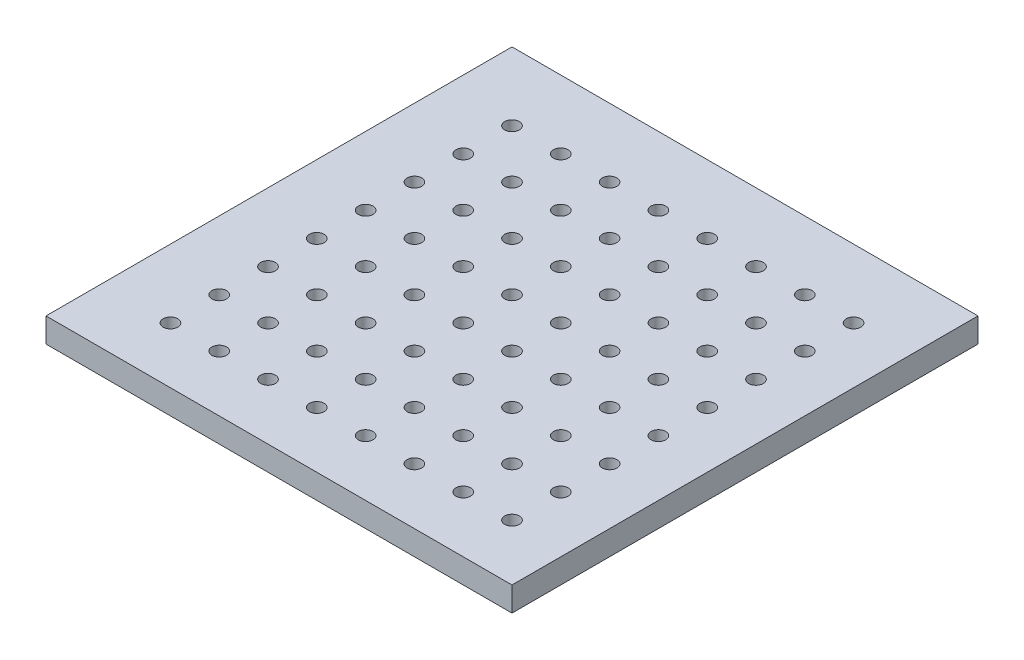
SolidWorks part; units mm, degrees
ref_plane "Front Plane" through (0, 0, 0) normal (0, 0, 1) x (1, 0, 0)
ref_plane "Top Plane" through (0, 0, 0) normal (0, 1, 0) x (1, 0, 0)
ref_plane "Right Plane" through (0, 0, 0) normal (1, 0, 0) x (0, 0, -1)
sketch "Sketch1" plane through (0, 0, 0) normal (0, 1, 0) x (1, 0, 0)
  line L0 (28, 163) -> (48, 163) construction
  line L1 (0, 0) -> (191, 0)
  line L2 (0, 0) -> (0, 191)
  line L3 (0, 191) -> (191, 191)
  line L4 (191, 0) -> (191, 191)
  line L5 (28, 163) -> (28, 143) construction
  circle A4 centre (28, 163) radius 3
  circle A5 centre (48, 163) radius 3
  circle A6 centre (68, 163) radius 3
  circle A7 centre (88, 163) radius 3
  circle A8 centre (108, 163) radius 3
  circle A22 centre (48, 143) radius 3
  circle A23 centre (68, 143) radius 3
  circle A24 centre (88, 143) radius 3
  circle A25 centre (108, 143) radius 3
  circle A39 centre (48, 123) radius 3
  circle A40 centre (68, 123) radius 3
  circle A41 centre (88, 123) radius 3
  circle A42 centre (108, 123) radius 3
  circle A56 centre (48, 103) radius 3
  circle A57 centre (68, 103) radius 3
  circle A58 centre (88, 103) radius 3
  circle A59 centre (108, 103) radius 3
  circle A73 centre (48, 83) radius 3
  circle A74 centre (68, 83) radius 3
  circle A75 centre (88, 83) radius 3
  circle A76 centre (108, 83) radius 3
  circle A311 centre (28, 143) radius 3
  circle A312 centre (28, 123) radius 3
  circle A313 centre (28, 103) radius 3
  circle A314 centre (28, 83) radius 3
  circle A328 centre (28, 63) radius 3
  circle A329 centre (48, 63) radius 3
  circle A330 centre (68, 63) radius 3
  circle A331 centre (88, 63) radius 3
  circle A332 centre (108, 63) radius 3
  circle A333 centre (28, 43) radius 3
  circle A334 centre (48, 43) radius 3
  circle A335 centre (68, 43) radius 3
  circle A336 centre (88, 43) radius 3
  circle A337 centre (108, 43) radius 3
  circle A338 centre (28, 23) radius 3
  circle A339 centre (48, 23) radius 3
  circle A340 centre (68, 23) radius 3
  circle A341 centre (88, 23) radius 3
  circle A342 centre (108, 23) radius 3
  circle A343 centre (128, 163) radius 3
  circle A344 centre (148, 163) radius 3
  circle A345 centre (168, 163) radius 3
  circle A346 centre (128, 143) radius 3
  circle A347 centre (148, 143) radius 3
  circle A348 centre (168, 143) radius 3
  circle A349 centre (128, 123) radius 3
  circle A350 centre (148, 123) radius 3
  circle A351 centre (168, 123) radius 3
  circle A352 centre (128, 103) radius 3
  circle A353 centre (148, 103) radius 3
  circle A354 centre (168, 103) radius 3
  circle A355 centre (128, 83) radius 3
  circle A356 centre (148, 83) radius 3
  circle A357 centre (168, 83) radius 3
  circle A358 centre (128, 63) radius 3
  circle A359 centre (148, 63) radius 3
  circle A360 centre (168, 63) radius 3
  circle A361 centre (128, 43) radius 3
  circle A362 centre (148, 43) radius 3
  circle A363 centre (168, 43) radius 3
  circle A364 centre (128, 23) radius 3
  circle A365 centre (148, 23) radius 3
  circle A366 centre (168, 23) radius 3
  point P7 (18.003, 169.1432)
  point P109 (0, 0)
  dimension "D7" = 6
  dimension "D1" = 191
  dimension "D2" = 191
  dimension "D5" = 20
  dimension "D6" = 20
  dimension "D8" = 28
  dimension "D9" = 28
  dimension "D3" = 8
  dimension "D4" = 8
extrude "Boss-Extrude1" add sketch "Sketch1" along normal blind 10
equation "\"x\" = 191"
equation "\"y\"= 191"
equation "\"D2@Sketch1\"=\"y\""
equation "\"D1@Sketch1\"=\"x\""
equation "\"# of Holes\" = 8"
equation "\"Hole Spacing\" = 20"
equation "\"Start Spacing\"= ( ( \"x\" - ( ( \"Hole Spacing\" ) * ( \"# of Holes\" - 1 ) ) ) / 2 ) - 3"
equation "\"D3@Sketch1\"=\"# of Holes\""
equation "\"D4@Sketch1\"=\"# of Holes\""
equation "\"D5@Sketch1\"=\"Hole Spacing\""
equation "\"D6@Sketch1\"=\"Hole Spacing\""
